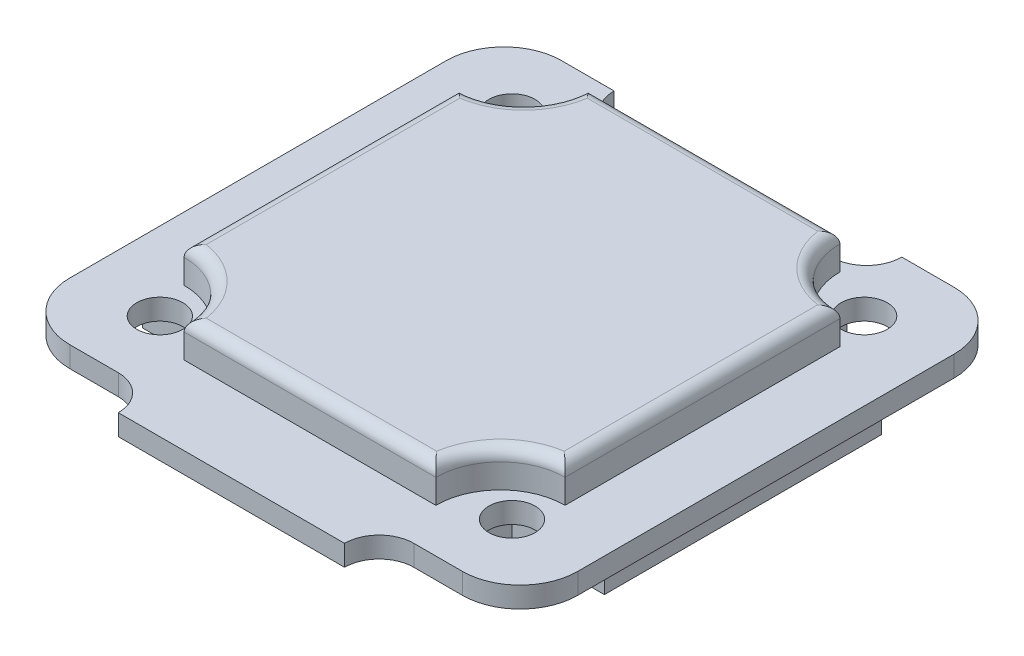
SolidWorks part; units mm, degrees
ref_plane "Płaszczyzna przednia" through (0, 0, 0) normal (0, 0, 1) x (1, 0, 0)
ref_plane "Płaszczyzna górna" through (0, 0, 0) normal (0, 1, 0) x (1, 0, 0)
ref_plane "Płaszczyzna prawa" through (0, 0, 0) normal (1, 0, 0) x (0, 0, -1)
sketch "Szkic1" plane through (0, 0, 0) normal (0, 1, 0) x (1, 0, 0)
  line L0 (0, -21.3) -> (0, -24.3) construction
  line L1 (-17, -21.3) -> (-12.8, -21.3)
  line L2 (-22, -16.3) -> (-22, 16.3)
  line L3 (-17, 21.3) -> (-12.4573, 21.3)
  line L4 (22, -16.3) -> (22, 16.3)
  line L5 (-22, -21.3) -> (22, 21.3) construction
  line L6 (-22, 21.3) -> (22, -21.3) construction
  line L7 (-15.25, -15.25) -> (15.25, -15.25) construction
  line L8 (-15.25, -15.25) -> (-15.25, 15.25) construction
  line L9 (-15.25, 15.25) -> (15.25, 15.25) construction
  line L10 (15.25, -15.25) -> (15.25, 15.25) construction
  line L11 (-15.25, -15.25) -> (15.25, 15.25) construction
  line L12 (-15.25, 15.25) -> (15.25, -15.25) construction
  line L13 (-9.8, -24.3) -> (9.8, -24.3)
  line L14 (9.8, -24.3) -> (12.8, -24.3) construction
  line L15 (-12.8, -21.3) -> (0, -21.3) construction
  line L16 (12.8, -21.3) -> (17, -21.3)
  line L17 (0, -21.3) -> (12.8, -21.3) construction
  line L18 (0, 21.3) -> (0, 18.3) construction
  line L19 (-10, 18.3) -> (10, 18.3)
  line L20 (-12.4573, 21.3) -> (0, 21.3) construction
  line L21 (12.4573, 21.3) -> (17, 21.3)
  line L22 (0, 21.3) -> (12.4573, 21.3) construction
  arc A0 (17, -21.3) -> (22, -16.3) centre (17, -16.3) ccw
  arc A1 (-17, -21.3) -> (-22, -16.3) centre (-17, -16.3) cw
  arc A2 (-22, 16.3) -> (-17, 21.3) centre (-17, 16.3) cw
  arc A3 (17, 21.3) -> (22, 16.3) centre (17, 16.3) cw
  circle A4 centre (15.25, 15.25) radius 2
  circle A5 centre (15.25, -15.25) radius 2
  circle A6 centre (-15.25, -15.25) radius 2
  circle A7 centre (-15.25, 15.25) radius 2
  arc A8 (9.8, -24.3) -> (12.8, -21.3) centre (12.8, -24.3) cw
  arc A9 (-9.8, -24.3) -> (-12.8, -21.3) centre (-12.8, -24.3) ccw
  arc A10 (10, 18.3) -> (12.4573, 21.3) centre (9.3974, 21.3) ccw
  arc A11 (-10, 18.3) -> (-12.4573, 21.3) centre (-9.3974, 21.3) cw
  point P0 (0, 0)
  point P18 (0, 0)
  point P33 (0, 0)
  point P36 (0, -24.3)
  point P45 (0, 18.3)
  dimension "D3" = 5
  dimension "D7" = 4
  dimension "D1" = 44
  dimension "D2" = 42.6
  dimension "D4" = 30.5
  dimension "D5" = 30.5
  dimension "D8" = 3
  dimension "D9" = 3
  dimension "D10" = 19.6
  dimension "D11" = 20
  dimension "D12" = 3
  dimension "D6" = 4
extrude "Dodanie-wyciągnięcie1" add sketch "Szkic1" along normal blind 1.8
sketch "Szkic2" plane through (0, 1.8, 0) normal (0, 1, 0) x (1, 0, 0)
  line L0 (-16.5, 0) -> (16.5, 0) construction
  line L1 (-10.9, -17.5) -> (10.9, -17.5)
  line L2 (-16.5, -11.9) -> (-16.5, 11.9)
  line L3 (-10.9, 17.5) -> (10.9, 17.5)
  line L4 (16.5, -11.9) -> (16.5, 11.9)
  line L5 (-16.5, -17.5) -> (16.5, 17.5) construction
  line L6 (-16.5, 17.5) -> (16.5, -17.5) construction
  line L7 (-16.5, 11.9) -> (-16.5, 17.5) construction
  line L8 (-16.5, 17.5) -> (-10.9, 17.5) construction
  line L9 (16.5, 11.9) -> (16.5, 17.5) construction
  line L10 (10.9, 17.5) -> (16.5, 17.5) construction
  line L11 (16.5, -17.5) -> (16.5, -11.9) construction
  line L12 (10.9, -17.5) -> (16.5, -17.5) construction
  line L13 (-16.5, -17.5) -> (-10.9, -17.5) construction
  line L14 (-16.5, -17.5) -> (-16.5, -11.9) construction
  arc A0 (-16.5, -11.9) -> (-10.9, -17.5) centre (-16.5, -17.5) cw
  arc A1 (16.5, -11.9) -> (10.9, -17.5) centre (16.5, -17.5) ccw
  arc A2 (16.5, 11.9) -> (10.9, 17.5) centre (16.5, 17.5) cw
  arc A3 (-16.5, 11.9) -> (-10.9, 17.5) centre (-16.5, 17.5) ccw
  point P0 (0, 0)
  point P13 (0, 0)
  dimension "D3" = 5.6
  dimension "D1" = 35
  dimension "D2" = 33
extrude "Dodanie-wyciągnięcie2" add sketch "Szkic2" along normal blind 3.1
fillet "Zaokrąglenie1" radius 1 8 edges at (-16.5, 4.9, 0) (-12.5402, 4.9, -13.5402) (0, 4.9, -17.5) (12.5402, 4.9, -13.5402) (16.5, 4.9, 0) (12.5402, 4.9, 13.5402) (0, 4.9, 17.5) (-12.5402, 4.9, 13.5402)
sketch "Szkic3" plane through (0, 0, 0) normal (0, -1, 0) x (1, 0, 0)
  line L0 (-12, 12) -> (-12, 7.2) construction
  line L1 (-12, 17) -> (12, 17)
  line L2 (-12, 17) -> (-12, 12)
  line L3 (-12, -17) -> (12, -17)
  line L4 (12, 17) -> (12, 12)
  line L5 (-12, 17) -> (12, -17) construction
  line L6 (-12, -17) -> (12, 17) construction
  line L7 (-20, -12) -> (-12, -12)
  line L8 (-20, -12) -> (-20, 12)
  line L9 (-20, 12) -> (-12, 12)
  line L10 (20, -12) -> (20, 12)
  line L11 (-20, -12) -> (20, 12) construction
  line L12 (-20, 12) -> (20, -12) construction
  line L13 (-12, 7.2) -> (-12, -7.2) construction
  line L14 (-12, 12) -> (-8.4706, 12) construction
  line L15 (-8.4706, 12) -> (8.4706, 12) construction
  line L16 (8.4706, 12) -> (12, 12) construction
  line L17 (12, 12) -> (20, 12)
  line L18 (12, 12) -> (12, 7.2) construction
  line L19 (12, -12) -> (12, -17)
  line L20 (12, 7.2) -> (12, -7.2) construction
  line L21 (12, -7.2) -> (12, -12) construction
  line L22 (8.4706, -12) -> (12, -12) construction
  line L23 (12, -12) -> (20, -12)
  line L24 (-8.4706, -12) -> (8.4706, -12) construction
  line L25 (-12, -12) -> (-8.4706, -12) construction
  line L26 (-12, -7.2) -> (-12, -12) construction
  line L27 (-12, -12) -> (-12, -17)
  point P0 (0, 0)
  point P6 (0, 0)
  dimension "D1" = 24
  dimension "D2" = 34
  dimension "D3" = 24
  dimension "D4" = 40
extrude "Dodanie-wyciągnięcie3" add sketch "Szkic3" along normal blind 3.1
